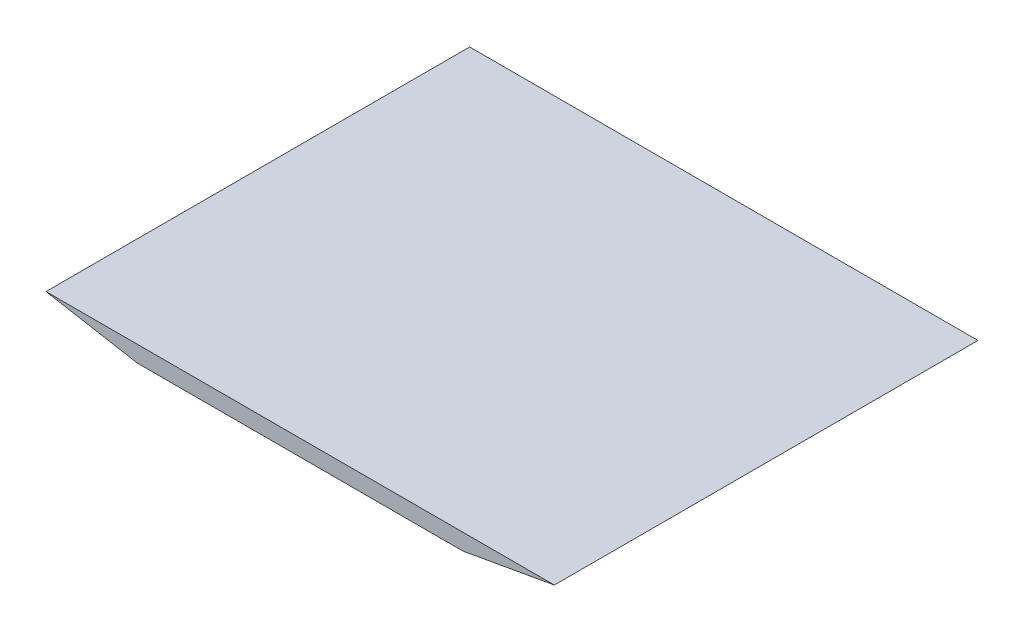
SolidWorks part; units mm, degrees
ref_plane "Front Plane" through (0, 0, 0) normal (0, 0, 1) x (1, 0, 0)
ref_plane "Top Plane" through (0, 0, 0) normal (0, 1, 0) x (1, 0, 0)
ref_plane "Right Plane" through (0, 0, 0) normal (1, 0, 0) x (0, 0, -1)
sketch "Sketch1" plane through (0, 0, 0) normal (0, 0, 1) x (1, 0, 0)
  line L0 (0, 0) -> (156, 0)
  line L1 (156, 0) -> (128, -5)
  line L2 (128, -5) -> (28, -5)
  line L3 (28, -5) -> (0, 0)
  dimension "D1" = 100
  dimension "D2" = 5
  dimension "D3" = 28
  dimension "D4" = 28
extrude "Boss-Extrude1" add sketch "Sketch1" along normal blind 130
